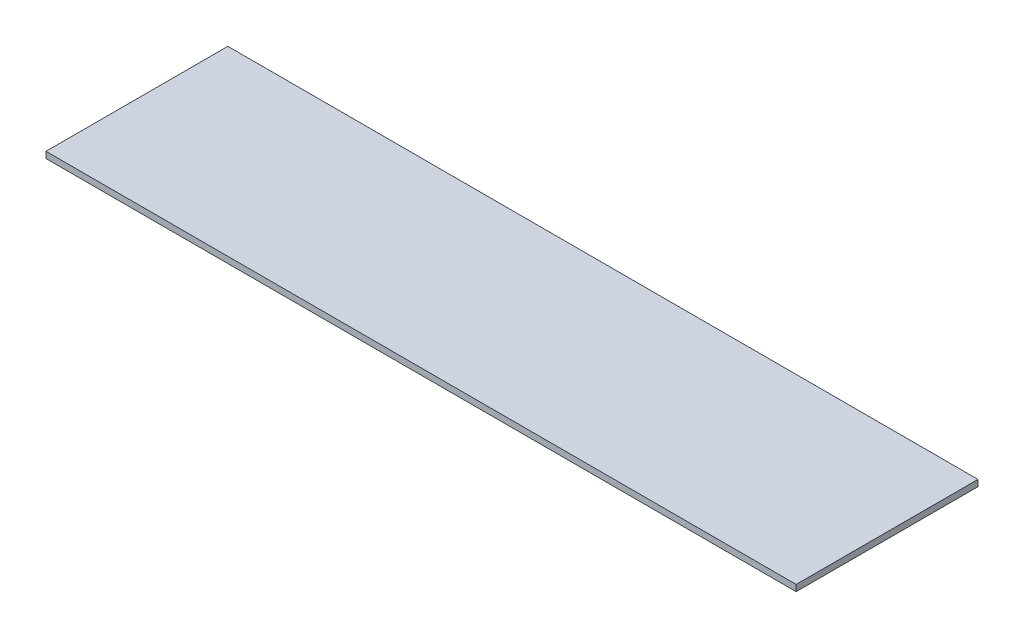
SolidWorks part; units mm, degrees
material "Teak"
ref_plane "Front Plane" through (0, 0, 0) normal (0, 0, 1) x (1, 0, 0)
ref_plane "Top Plane" through (0, 0, 0) normal (0, 1, 0) x (1, 0, 0)
ref_plane "Right Plane" through (0, 0, 0) normal (1, 0, 0) x (0, 0, -1)
sketch "Sketch1" plane through (0, 0, 0) normal (0, 1, 0) x (1, 0, 0)
  line L1 (0, 0) -> (594, 0)
  line L2 (0, 0) -> (0, 144)
  line L3 (0, 144) -> (594, 144)
  line L4 (594, 0) -> (594, 144)
  dimension "D1" = 144
  dimension "D2" = 594
extrude "Boss-Extrude1" add sketch "Sketch1" along normal blind 5
